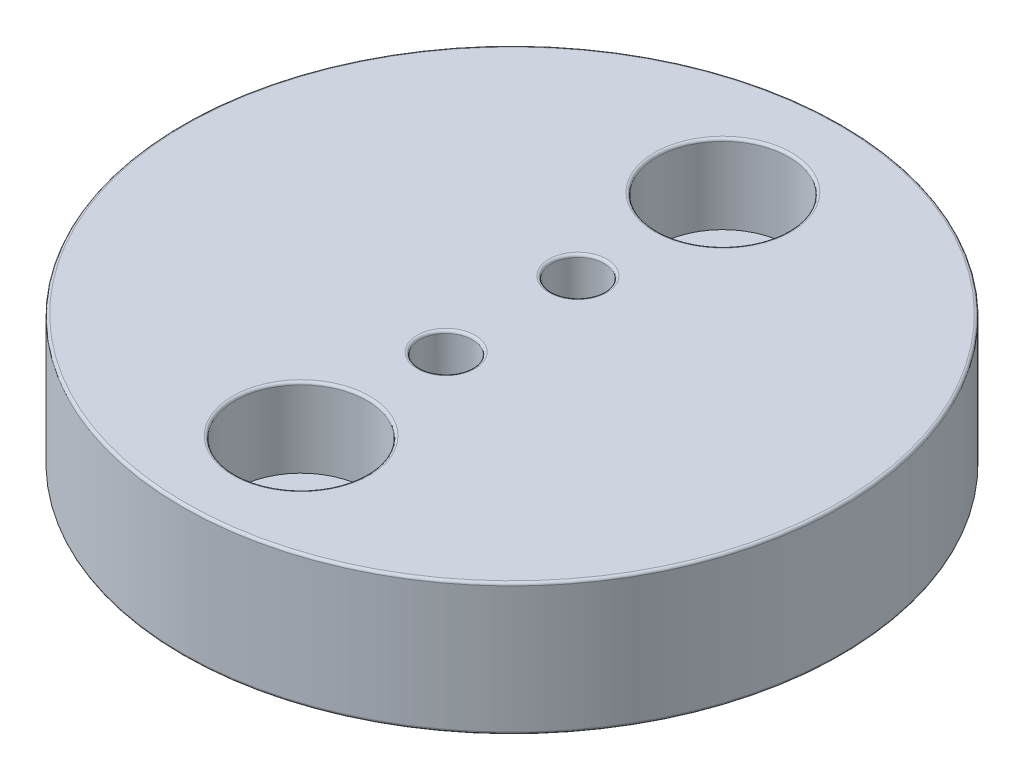
SolidWorks part; units mm, degrees
ref_plane "前视基准面" through (0, 0, 0) normal (0, 0, 1) x (1, 0, 0)
ref_plane "上视基准面" through (0, 0, 0) normal (0, 1, 0) x (1, 0, 0)
ref_plane "右视基准面" through (0, 0, 0) normal (1, 0, 0) x (0, 0, -1)
other "Configuration Table"
sketch "草图1" plane through (0, 0, 0) normal (0, 1, 0) x (1, 0, 0)
  circle A0 centre (0, 0) radius 12.5
  circle A1 centre (0, 0) radius 8 construction
  circle A2 centre (0, 8) radius 1.25
  circle A3 centre (0, -8) radius 1.25
  dimension "D1" = 16
  dimension "D2" = 2.5
  dimension "D3" = 2.5
  dimension "D4" = 25
extrude "凸台-拉伸1" add sketch "草图1" along normal blind 5
sketch "草图3" plane through (0, 5, 0) normal (0, 1, 0) x (1, 0, 0)
  line L0 (0, 2.5) -> (0, -2.5) construction
  circle A0 centre (0, 2.5) radius 1
  circle A1 centre (0, -2.5) radius 1
  dimension "D1" = 2
  dimension "D2" = 2
  dimension "D3" = 5
  dimension "D4" = 2.5
extrude "切除-拉伸1" cut sketch "草图3" against normal up to next
sketch "草图4" plane through (0, 5, 0) normal (0, 1, 0) x (1, 0, 0)
  circle A0 centre (0, 8) radius 2.5
  circle A1 centre (0, -8) radius 2.5
  dimension "D1" = 5
  dimension "D2" = 5
extrude "切除-拉伸2" cut sketch "草图4" against normal blind 3
sketch "草图5" plane through (0, 0, 0) normal (0, -1, 0) x (1, 0, 0)
  circle A0 centre (0, 2.5) radius 1.65
  circle A1 centre (0, -2.5) radius 1.65
  dimension "D1" = 3.3
  dimension "D2" = 3.3
extrude "切除-拉伸3" cut sketch "草图5" against normal blind 3.2
fillet "圆角1" radius 0.1 14 edges at (0, 3.2, -3.5) (0, 3.2, 1.5) (0, 2, -6.75) (0, 2, 9.25) (0, 0, 9.25) (0, 0, -6.75) (0, 0, -4.15) (0, 0, 0.85) (0, 5, 3.5) (0, 5, -1.5) (0, 5, 10.5) (0, 5, -5.5) (0, 0, 12.5) (0, 5, 12.5)
